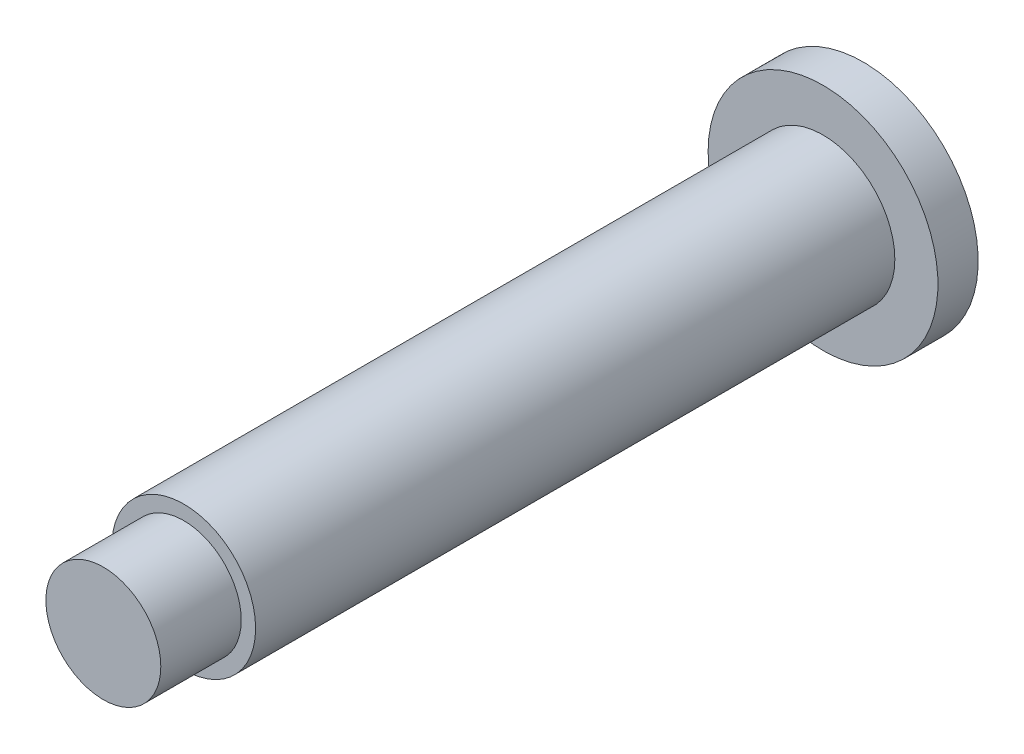
SolidWorks part; units mm, degrees
ref_plane "Front Plane" through (0, 0, 0) normal (1, 0, 0) x (0, 1, 0)
ref_plane "Top Plane" through (0, 0, 0) normal (0, 0, 1) x (0, 1, 0)
ref_plane "Right Plane" through (0, 0, 0) normal (0, 1, 0) x (-1, 0, 0)
sketch "Sketch1" plane through (0, 0, 0) normal (0, 0, 1) x (0, 1, 0)
  circle A0 centre (0, 0) radius 2.5
  dimension "D1" = 5
extrude "Boss-Extrude1" add sketch "Sketch1" along normal blind 22.25 contours A0
sketch "Sketch2" plane through (0, 0, 0) normal (0, 0, -1) x (1, 0, 0)
  circle A0 centre (0, 0) radius 4
  dimension "D1" = 8
extrude "Boss-Extrude2" add sketch "Sketch2" along normal blind 1.4
sketch "Sketch3" plane through (0, 0, -1.4) normal (0, 0, -1) x (1, 0, 0)
  circle A0 centre (0, 0) radius 2.05
  dimension "D1" = 4.1
extrude "Cut-Extrude1" cut sketch "Sketch3" against normal blind 3
sketch "Sketch4" plane through (0, 0, 22.25) normal (0, 0, 1) x (1, 0, 0)
  circle A0 centre (0, 0) radius 2
  dimension "D1" = 4
extrude "Boss-Extrude3" add sketch "Sketch4" along normal blind 2.8
equation "\"whitekey_cutout_length\"= 101.5"
equation "\"key_mount_recess_length\"=50"
equation "\"key_mount_recess_height\"=12.5"
equation "\"key_mount_recess_depth\"=1.5"
equation "\"wall_thickness\"=10"
equation "\"guide_brace_height\"=20"
equation "\"guide_brace_thickness\"=2"
equation "\"dowel_recess_depth\"=9"
equation "\"dowel_recess_offset\"=3.25"
equation "\"base_mount_height\"=40"
equation "\"base_rear_length\"=80"
equation "\"base_front_length\"=111.5"
equation "\"screw_hole_wall_offset\"=7.25"
equation "\"screw_hole_edge_inset\"=4.5"
equation "\"screw_hole_diameter\"=3.8"
equation "\"screw_head_hole_diameter\"=6.7"
equation "\"screw_nut_hole_side_len\"=3.5"
equation "\"screw_nut_recess_offset\"=0.4"
equation "\"screw_head_and_nut_recess_depth\"=2.5"
equation "\"screw_shaft_diameter\"=3.5"
equation "\"switch_board_width\"=30"
equation "\"switch_board_wall_offset\"=11.5"
equation "\"heatset_insert_hole_diameter\"=4.8"
equation "\"heatset_insert_hole_depth\"=3.8"
equation "\"front_rear_panel_width\"=23.75"
equation "\"rod_length_adj\"=0.5"
equation "\"rod_insert_length\"=2.8"
equation "\"D1@Boss-Extrude1\"=\"rod_length_adj\"+21.75mm"
equation "\"D1@Boss-Extrude2\"=2-\"rod_length_adj\"-0.1"
equation "\"D1@Boss-Extrude3\"=\"rod_insert_length\""
equation "\"switch_board_thickness\"=1.6"
equation "\"rod_diameter\"=5"
equation "\"rod_head_diameter\"=8"
equation "\"switch_black_key_mount_height\"=8"
equation "\"switch_white_key_mount_height\"=3"
equation "\"D1@Sketch1\"=\"rod_diameter\""
equation "\"D1@Sketch2\"=\"rod_head_diameter\""
equation "\"D1@Sketch3\"=\"rod_diameter\"-1+0.1"
equation "\"D1@Sketch4\"=\"rod_diameter\"-1"
